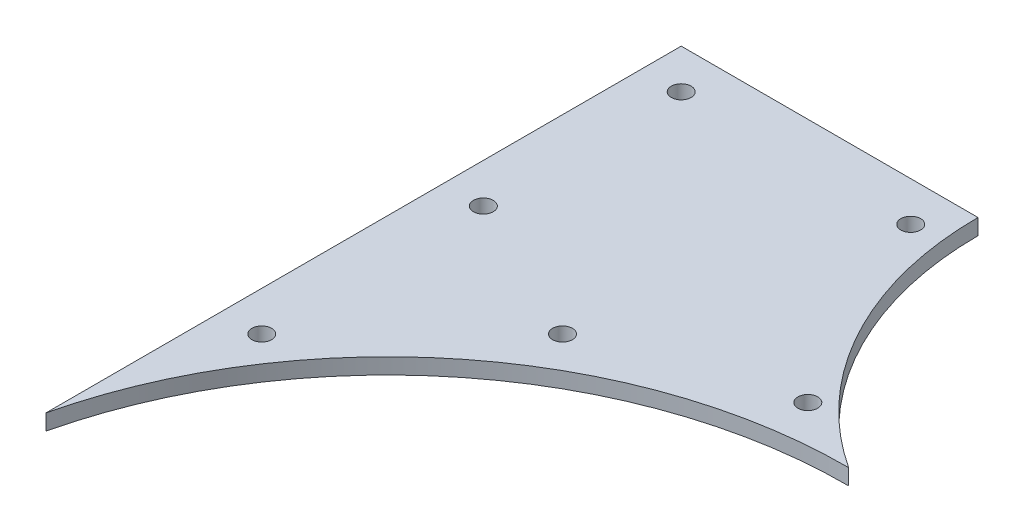
SolidWorks part; units mm, degrees
ref_plane "Front Plane" through (0, 0, 0) normal (0, 0, 1) x (1, 0, 0)
ref_plane "Top Plane" through (0, 0, 0) normal (0, 1, 0) x (1, 0, 0)
ref_plane "Right Plane" through (0, 0, 0) normal (1, 0, 0) x (0, 0, -1)
sketch "Sketch1" plane through (0, 0, 0) normal (0, 1, 0) x (1, 0, 0)
  line L1 (0, 0) -> (381, 0)
  line L2 (0, 0) -> (0, 381)
  line L3 (0, 381) -> (381, 381)
  line L4 (381, 0) -> (381, 381)
  line L5 (0, 381) -> (-203.2, 381)
  line L6 (0, 381) -> (0, 0)
  line L7 (0, 0) -> (-203.2, 0)
  line L8 (-203.2, 381) -> (-203.2, 0)
  arc A0 (381, 381) -> (0, 0) centre (0, 381) cw
  circle A1 centre (39.2386, 142.9117) radius 139.7
  circle A2 centre (0, 381) radius 101.6
  circle A3 centre (196.7476, 241.3) radius 139.7
  circle A4 centre (86.3584, 155.6826) radius 139.7
  circle A5 centre (-59.7956, 143.4044) radius 143.4044
  circle A6 centre (0, 381) radius 107.95
  circle A7 centre (-59.7956, 143.4044) radius 147.32
  dimension "D1" = 381
  dimension "D2" = 381
  dimension "D3" = 203.2
extrude "Boss-Extrude1" add sketch "Sketch1" along normal blind 5.08 contours A5 A2 L5 L8
sketch "Sketch2" plane through (0, 5.08, 0) normal (0, 1, 0) x (1, 0, 0)
  line L0 (-107.95, 381) -> (-203.2, 381) construction
  line L1 (-203.2, 381) -> (-203.2, 177.1439) construction
  circle A0 centre (-190.5, 233.68) radius 3.175
  circle A1 centre (-83.82, 302.26) radius 3.175
  circle A2 centre (-116.84, 368.3) radius 3.175
  circle A3 centre (-190.5, 368.3) radius 3.175
  circle A4 centre (-142.24, 281.94) radius 3.175
  circle A5 centre (-190.5, 304.8) radius 3.175
  point P18 (-115.3808, 366.8701)
  dimension "D1" = 12.7
  dimension "D2" = 12.7
  dimension "D3" = 12.7
  dimension "D4" = 86.36
  dimension "D5" = 78.74
  dimension "D6" = 119.38
  dimension "D7" = 99.06
  dimension "D8" = 60.96
  dimension "D9" = 147.32
  dimension "D10" = 12.7
  dimension "D11" = 12.7
  dimension "D12" = 76.2
extrude "Cut-Extrude1" cut sketch "Sketch2" against normal blind 5.08
